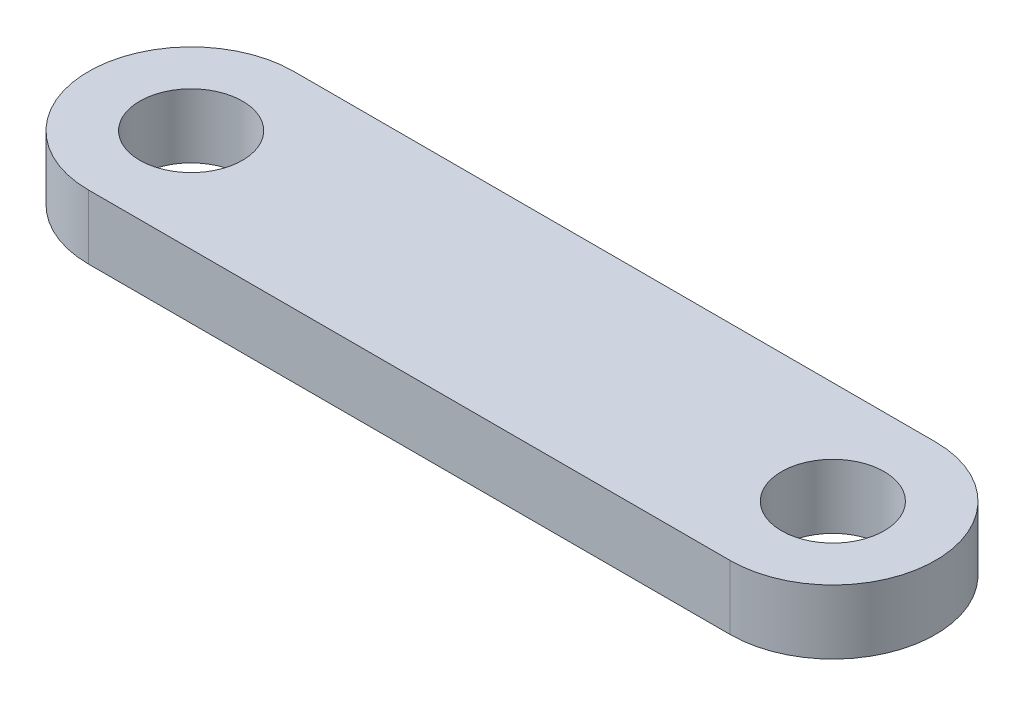
SolidWorks part; units mm, degrees
ref_plane "Front Plane" through (0, 0, 0) normal (0, 0, 1) x (1, 0, 0)
ref_plane "Top Plane" through (0, 0, 0) normal (0, 1, 0) x (1, 0, 0)
ref_plane "Right Plane" through (0, 0, 0) normal (1, 0, 0) x (0, 0, -1)
sketch "Sketch1" plane through (0, 0, 0) normal (0, 1, 0) x (1, 0, 0)
  line L1 (-25, -8) -> (25, -8)
  line L3 (-25, 8) -> (25, 8)
  line L5 (-25, -8) -> (25, 8) construction
  line L6 (-25, 8) -> (25, -8) construction
  arc A0 (-25, 8) -> (-25, -8) centre (-25, 0) ccw
  arc A1 (25, 8) -> (25, -8) centre (25, 0) cw
  circle A2 centre (-25, 0) radius 4
  circle A3 centre (25, 0) radius 4
  point P0 (0, 0)
  dimension "D2" = 8
  dimension "D3" = 8
  dimension "D1" = 50
extrude "Boss-Extrude1" add sketch "Sketch1" along normal blind 5
